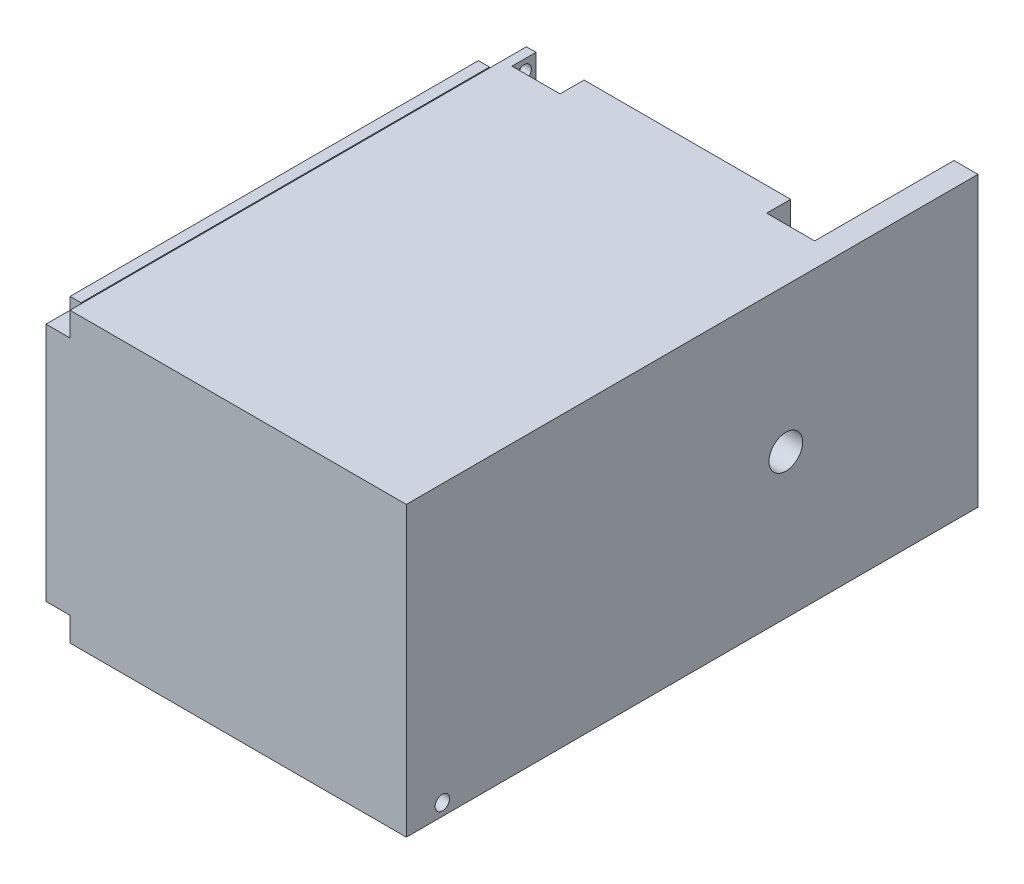
SolidWorks part; units mm, degrees
material "Alliage 1060"
ref_plane "Plan de dessus" through (0, 0, 0) normal (0, 0, 1) x (1, 0, 0)
ref_plane "Plan de droite" through (0, 0, 0) normal (0, 1, 0) x (1, 0, 0)
ref_plane "Plan de face" through (0, 0, 0) normal (1, 0, 0) x (0, 0, -1)
sketch "Esquisse1" plane through (0, 0, 0) normal (0, 0, 1) x (1, 0, 0)
  line L5 (0, 0) -> (75, 0)
  line L6 (0, 0) -> (0, 60)
  line L7 (0, 60) -> (75, 60)
  line L8 (75, 0) -> (75, 60)
  line L12 (7, 0) -> (7, 55)
  line L13 (7, 55) -> (70, 55)
  line L14 (70, 55) -> (70, 0)
  line L16 (7, 0) -> (70, 0)
  dimension "D1" = 7
  dimension "D2" = 5
  dimension "D3" = 60
  dimension "D4" = 5
extrude "volume boitier" add sketch "Esquisse1" along normal blind 90
sketch "Esquisse2" plane through (0, 0, 90) normal (0, 0, 1) x (1, 0, 0)
  line L1 (0, 60) -> (75, 60)
  line L2 (0, 60) -> (0, 0)
  line L3 (0, 0) -> (75, 0)
  line L4 (75, 60) -> (75, 0)
extrude "face inférieure" add sketch "Esquisse2" along normal blind 5
sketch "Esquisse3" plane through (0, 0, 0) normal (0, 0, -1) x (-1, 0, 0)
  line L0 (-70, 60) -> (-70, 0)
  line L1 (-75, 60) -> (-70, 60)
  line L2 (-75, 60) -> (-75, 0)
  line L5 (-70, 0) -> (-75, 0)
extrude "face pile" add sketch "Esquisse3" along normal blind 24
sketch "Esquisse11" plane through (75, 0, 0) normal (1, 0, 0) x (0, 0, -1)
  line L0 (24, 60) -> (24, 0) construction
  line L5 (-95, 0) -> (-95, 60) construction
  line L6 (-16, 60) -> (-16, 0) construction
  line L7 (-95, 60) -> (24, 60) construction
  line L8 (-95, 0) -> (24, 0) construction
  line L10 (-95, 0) -> (24, 0) construction
  circle A1 centre (-16, 30) radius 3.5
  circle A2 centre (-87.5, 2.5) radius 1.5
  dimension "D1" = 7
  dimension "D3" = 3
  dimension "D4" = 7.5
  dimension "D2" = 40
  dimension "D5" = 2.5
extrude "Enlèv. mat.-Extru.6" cut sketch "Esquisse11" against normal up to next
sketch "Esquisse12" plane through (0, 0, 90) normal (0, 0, -1) x (-1, 0, 0)
  line L5 (-70, 0) -> (-70, 60) construction
  line L24 (-70, 20) -> (-70, 23)
  line L31 (-70, 23) -> (-27, 23)
  line L33 (-29, 20) -> (-70, 20)
  line L34 (-7, 55) -> (-70, 55) construction
  line L36 (-27, 15) -> (-29, 15)
  line L37 (-29, 15) -> (-29, 20)
  line L38 (-27, 23) -> (-27, 15)
  line L40 (-70, 7) -> (-67, 7)
  line L41 (-70, 7) -> (-70, 5)
  line L42 (-70, 5) -> (-67, 5)
  line L43 (-67, 7) -> (-67, 5)
  line L44 (-7, 55) -> (-7, 0) construction
  line L45 (-7, 7) -> (-10, 7)
  line L46 (-7, 7) -> (-7, 5)
  line L47 (-7, 5) -> (-10, 5)
  line L48 (-10, 7) -> (-10, 5)
  line L49 (-7, 0) -> (-70, 0) construction
  dimension "D12" = 41
  dimension "D2" = 8
  dimension "D3" = 32
  dimension "D4" = 2
  dimension "D5" = 3
  dimension "D6" = 5
  dimension "D7" = 2
  dimension "D8" = 3
  dimension "D9" = 5
  dimension "D10" = 3
  dimension "D11" = 2
extrude "Boss.-Extru.7" add sketch "Esquisse12" along normal offset from surface (85 mm away) 5 up to face at (25.6667, 38.3333, 0)
sketch "Esquisse13" plane through (0, 0, 0) normal (-1, 0, 0) x (0, 0, 1)
  line L0 (95, 0) -> (0, 0) construction
  line L1 (0, 0) -> (0, 60) construction
  line L2 (95, 60) -> (0, 60) construction
  circle A0 centre (2.5, 2.5) radius 1.5
  circle A1 centre (2.5, 57.5) radius 1.527
  dimension "D1" = 3
  dimension "D4" = 3.0541
  dimension "D2" = 2.5
  dimension "D3" = 2.5
  dimension "D5" = 2.5
  dimension "D6" = 2.5
extrude "Enlèv. mat.-Extru.7" cut sketch "Esquisse13" against normal blind 20
sketch "Esquisse14" plane through (0, 0, 0) normal (0, 0, -1) x (-1, 0, 0)
  line L0 (-7, 55) -> (-70, 55) construction
  line L1 (-70, 60) -> (-60, 60)
  line L2 (-70, 60) -> (-70, 55)
  line L3 (-70, 55) -> (-60, 55)
  line L4 (-60, 60) -> (-60, 55)
  line L5 (0, 60) -> (-70, 60) construction
  line L6 (-7, 55) -> (-17, 55)
  line L7 (-7, 55) -> (-7, 60)
  line L8 (-7, 60) -> (-17, 60)
  line L9 (-17, 55) -> (-17, 60)
  line L10 (-70, 0) -> (-70, 60) construction
  dimension "D1" = 10
  dimension "D2" = 10
extrude "Enlèv. mat.-Extru.8" cut sketch "Esquisse14" against normal blind 5
sketch "Esquisse15" plane through (0, 20, 0) normal (0, -1, 0) x (1, 0, 0)
  line L0 (7, 90) -> (70, 90) construction
  line L1 (7, 90) -> (7, 0) construction
  circle A0 centre (33, 70) radius 1.1
  dimension "D1" = 20
  dimension "D3" = 2.2
  dimension "D2" = 26
extrude "Enlèv. mat.-Extru.9" cut sketch "Esquisse15" against normal up to next
sketch "Esquisse16" plane through (0, 0, 95) normal (0, 0, 1) x (1, 0, 0)
  line L0 (0, 2.5) -> (2.3, 2.5)
  line L1 (0, 60) -> (0, 0) construction
  line L2 (2.3, 2.5) -> (2.3, 5)
  line L3 (2.3, 5) -> (5, 5)
  line L4 (5, 5) -> (5, 0)
  line L5 (0, 0) -> (75, 0) construction
  line L6 (5, 0) -> (0, 0)
  line L7 (0, 0) -> (0, 2.5)
  line L8 (0, 30) -> (10.2022, 30) construction
  line L9 (0, 60) -> (0, 57.5)
  line L10 (5, 60) -> (0, 60)
  line L11 (5, 55) -> (5, 60)
  line L12 (2.3, 55) -> (5, 55)
  line L13 (2.3, 57.5) -> (2.3, 55)
  line L14 (0, 57.5) -> (2.3, 57.5)
  dimension "D1" = 5
  dimension "D2" = 5
  dimension "D3" = 2.3
  dimension "D4" = 2.5
extrude "Enlèv. mat.-Extru.10" cut sketch "Esquisse16" against normal offset from surface (90 mm away) 5 up to face at (3.5, 30, 0)
sketch "Esquisse17" plane through (0, 0, 0) normal (-1, 0, 0) x (0, 0, 1)
  line L0 (0, 0) -> (5, 0)
  line L1 (0, 60) -> (5, 60)
  line L2 (0, 60) -> (0, 55)
  line L3 (0, 55) -> (5, 55)
  line L4 (5, 60) -> (5, 55)
  line L5 (5, 0) -> (5, 5)
  line L6 (5, 5) -> (0, 5)
  line L7 (0, 0) -> (0, 60) construction
  line L8 (0, 5) -> (0, 0)
  dimension "D1" = 5
  dimension "D2" = 5
  dimension "D3" = 5
extrude "Enlèv. mat.-Extru.11" cut sketch "Esquisse17" against normal blind 5
sketch "Esquisse18" plane through (0, 0, 95) normal (0, 0, 1) x (1, 0, 0)
  line L0 (0, 57.5) -> (0, 2.5) construction
  line L1 (2.3, 2.5) -> (0, 2.5)
  line L2 (2.3, 2.5) -> (2.3, 5)
  line L3 (2.3, 5) -> (0, 5)
  line L4 (0, 2.5) -> (0, 5)
  line L6 (0, 57.5) -> (2.3, 57.5)
  line L7 (0, 57.5) -> (0, 55)
  line L8 (0, 55) -> (2.3, 55)
  line L9 (2.3, 57.5) -> (2.3, 55)
extrude "Enlèv. mat.-Extru.12" cut sketch "Esquisse18" against normal blind 5
sketch "Esquisse20" plane through (0, 0, 0) normal (-1, 0, 0) x (0, 0, 1)
  line L0 (67.5, 37.5) -> (67.5, 57.5) construction
  line L1 (20, 37.5) -> (35, 37.5)
  line L2 (20, 37.5) -> (20, 22.5)
  line L3 (20, 22.5) -> (35, 22.5)
  line L4 (35, 37.5) -> (35, 22.5)
  line L5 (60, 37.5) -> (75, 37.5)
  line L6 (60, 37.5) -> (60, 22.5)
  line L7 (60, 22.5) -> (75, 22.5)
  line L8 (75, 37.5) -> (75, 22.5)
  line L9 (5, 57.5) -> (90, 57.5) construction
  line L10 (67.5, 22.5) -> (67.5, 2.5) construction
  line L11 (5, 2.5) -> (90, 2.5) construction
  line L12 (27.5, 37.5) -> (27.5, 57.5) construction
  line L13 (27.5, 22.5) -> (27.5, 2.5) construction
  line L14 (0, 5) -> (0, 55) construction
  line L15 (95, 55) -> (95, 5) construction
  dimension "D1" = 15
  dimension "D2" = 20
  dimension "D3" = 20
extrude "Enlèv. mat.-Extru.13" cut sketch "Esquisse20" against normal up to next
sketch "Esquisse21" plane through (0, 20, 0) normal (0, -1, 0) x (1, 0, 0)
  line L0 (57, 67) -> (70, 67) construction
  line L1 (42, 72) -> (57, 72)
  line L2 (42, 72) -> (42, 62)
  line L3 (42, 62) -> (57, 62)
  line L4 (57, 72) -> (57, 62)
  line L6 (42, 67) -> (29, 67) construction
  line L7 (29, 5) -> (29, 90) construction
  line L8 (70, 90) -> (29, 90) construction
  line L9 (70, 5) -> (70, 90) construction
  dimension "D1" = 10
  dimension "D2" = 15
  dimension "D3" = 18
extrude "Enlèv. mat.-Extru.14" cut sketch "Esquisse21" against normal up to next
sketch "Esquisse22" plane through (0, 5, 0) normal (0, -1, 0) x (1, 0, 0)
  line L0 (5, 95) -> (0, 95) construction
  line L1 (0, 90) -> (0, 95) construction
  circle A0 centre (2.5, 92.5) radius 1.5
  dimension "D1" = 3
  dimension "D2" = 2.5
  dimension "D3" = 2.5
extrude "Enlèv. mat.-Extru.15" cut sketch "Esquisse22" against normal blind 10
